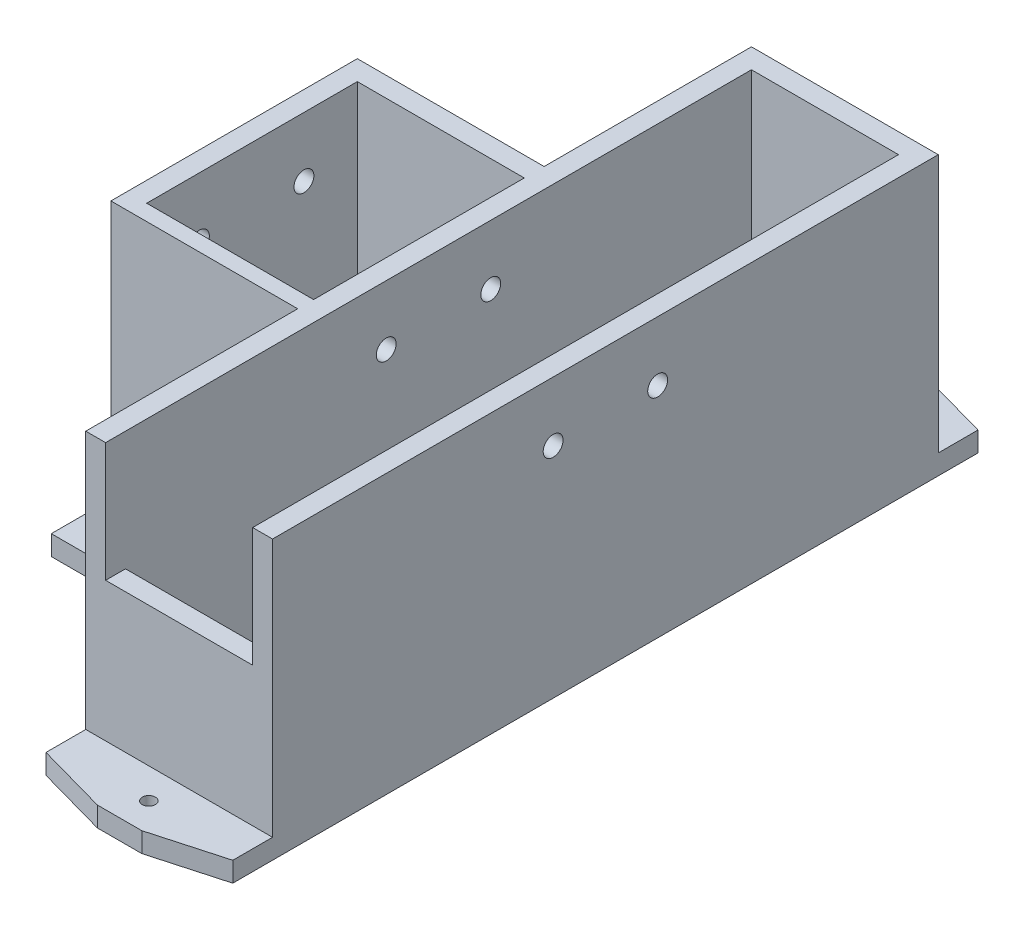
SolidWorks part; units mm, degrees
ref_plane "Plano frontal" through (0, 0, 0) normal (0, 0, 1) x (1, 0, 0)
ref_plane "Plano superior" through (0, 0, 0) normal (0, 1, 0) x (1, 0, 0)
ref_plane "Plano direito" through (0, 0, 0) normal (1, 0, 0) x (0, 0, -1)
sketch "Esboço1" plane through (0, 0, 0) normal (0, 1, 0) x (1, 0, 0)
  line L0 (9.0777, 0.5851) -> (55.4959, 0.5851) construction
  line L1 (0, 0) -> (0, -30.0205) construction
  line L3 (-23.5, 83.75) -> (23.5, 83.75)
  line L4 (-23.5, 83.75) -> (-23.5, -83.75)
  line L5 (-23.5, -83.75) -> (23.5, -83.75)
  line L6 (23.5, 83.75) -> (23.5, -83.75)
  line L7 (-23.5, 83.75) -> (23.5, -83.75) construction
  line L8 (-23.5, -83.75) -> (23.5, 83.75) construction
  line L9 (-70.5, 31.5851) -> (-23.5, 31.5851)
  line L10 (-70.5, 31.5851) -> (-70.5, -30.4149)
  line L11 (-70.5, -30.4149) -> (-23.5, -30.4149)
  line L12 (-23.5, 31.5851) -> (-23.5, -30.4149)
  line L13 (-70.5, 31.5851) -> (-23.5, -30.4149) construction
  line L14 (-70.5, -30.4149) -> (-23.5, 31.5851) construction
  point P1 (0, 0)
  point P11 (-47, 0.5851)
  dimension "D1" = 47
  dimension "D2" = 167.5
  dimension "D3" = 47
  dimension "D4" = 62
extrude "Ressalto-extrusão1" add sketch "Esboço1" along normal blind 70 contours L10 L11 L4 L9 | L6 L3 L4 L5
sketch "Esboço3" plane through (0, 70, 0) normal (0, 1, 0) x (1, 0, 0)
  line L0 (-23.5, 83.75) -> (23.5, 83.75) construction
  line L1 (18.5, -78.75) -> (-18.5, -78.75)
  line L2 (18.5, -78.75) -> (18.5, 78.75)
  line L3 (18.5, 78.75) -> (-18.5, 78.75)
  line L4 (-18.5, -78.75) -> (-18.5, 78.75)
  line L5 (18.5, -78.75) -> (-18.5, 78.75) construction
  line L6 (18.5, 78.75) -> (-18.5, -78.75) construction
  line L7 (-23.5, 83.75) -> (-23.5, 31.5851) construction
  point P0 (0, 0)
  dimension "D1" = 157.5
  dimension "D2" = 5
  dimension "D3" = 37
  dimension "D4" = 5
extrude "Corte-extrusão2" cut sketch "Esboço3" against normal blind 65
sketch "Esboço5" plane through (0, 70, 0) normal (0, 1, 0) x (1, 0, 0)
  line L0 (-18.5, -78.75) -> (18.5, -78.75) construction
  line L1 (-18.5, -62.7828) -> (18.5, -62.7828)
  line L2 (-18.5, -62.7828) -> (-18.5, -94.7172)
  line L3 (-18.5, -94.7172) -> (18.5, -94.7172)
  line L4 (18.5, -62.7828) -> (18.5, -94.7172)
  line L5 (-18.5, -62.7828) -> (18.5, -94.7172) construction
  line L6 (-18.5, -94.7172) -> (18.5, -62.7828) construction
  point P0 (0, -78.75)
  dimension "D1" = 37
extrude "Corte-extrusão3" cut sketch "Esboço5" against normal blind 30
sketch "Esboço11" plane through (0, 0, 0) normal (0, -1, 0) x (1, 0, 0)
  line L0 (-23.5, -83.75) -> (-23.5, -31.5851) construction
  line L1 (-23.5, -83.75) -> (23.5, -83.75)
  line L2 (-23.5, -83.75) -> (-23.5, -98.75)
  line L3 (-23.5, -98.75) -> (23.5, -98.75)
  line L4 (23.5, -83.75) -> (23.5, -98.75)
  line L5 (-23.5, 83.75) -> (23.5, 83.75)
  line L6 (-23.5, 83.75) -> (-23.5, 98.75)
  line L7 (-23.5, 98.75) -> (23.5, 98.75)
  line L8 (23.5, 83.75) -> (23.5, 98.75)
  line L9 (-70.5, -31.5851) -> (-23.5, -31.5851)
  line L10 (-70.5, -31.5851) -> (-70.5, -46.5851)
  line L11 (-70.5, -46.5851) -> (-23.5, -46.5851)
  line L12 (-23.5, -31.5851) -> (-23.5, -46.5851)
  line L13 (-23.5, 30.4149) -> (-23.5, 83.75) construction
  line L14 (-70.5, 30.4149) -> (-23.5, 30.4149)
  line L15 (-70.5, 30.4149) -> (-70.5, 45.4149)
  line L16 (-70.5, 45.4149) -> (-23.5, 45.4149)
  line L17 (-23.5, 30.4149) -> (-23.5, 45.4149)
  dimension "D1" = 15
  dimension "D2" = 15
  dimension "D3" = 15
  dimension "D4" = 15
extrude "Ressalto-extrusão2" add sketch "Esboço11" against normal blind 5
sketch "Esboço12" plane through (0, 5, 0) normal (0, 1, 0) x (1, 0, 0)
  line L0 (-70.5, 46.5851) -> (-23.5, 46.5851) construction
  line L1 (-23.5, -45.4149) -> (-70.5, -45.4149) construction
  line L2 (-70.5, 31.5851) -> (-70.5, 46.5851) construction
  line L4 (-70.5, -45.4149) -> (-70.5, -30.4149) construction
  line L5 (23.5, -98.75) -> (-23.5, -98.75) construction
  line L6 (-23.5, 98.75) -> (23.5, 98.75) construction
  circle A0 centre (-47, -38.0499) radius 1.65
  circle A2 centre (-47, 39.2151) radius 1.65
  circle A4 centre (0, -91.38) radius 1.65
  circle A5 centre (0, 91.38) radius 1.65
  point P20 (0, -98.75)
  dimension "D1" = 3.3
  dimension "D5" = 3.3
  dimension "D11" = 3.3
  dimension "D13" = 3.3
  dimension "D4" = 7.37
  dimension "D8" = 7.365
  dimension "D9" = 23.5
  dimension "D10" = 23.5
  dimension "D12" = 7.37
  dimension "D14" = 7.37
extrude "Corte-extrusão6" cut sketch "Esboço12" against normal through all
sketch "Esboço14" plane through (23.5, 0, 0) normal (1, 0, 0) x (0, 0, -1)
  line L0 (0, 0) -> (0, 98.479) construction
  line L1 (83.75, 70) -> (-83.75, 70) construction
  circle A0 centre (-13.15, 55) radius 2.5
  circle A1 centre (13.15, 55) radius 2.5
  dimension "D1" = 26.3
  dimension "D2" = 5
  dimension "D3" = 5
  dimension "D4" = 13.15
  dimension "D5" = 15
  dimension "D6" = 15
extrude "Corte-extrusão8" cut sketch "Esboço14" against normal through all
sketch "Esboço15" plane through (0, 70, 0) normal (0, 1, 0) x (1, 0, 0)
  line L1 (-65.5, 26.5851) -> (-23.5, 26.5851)
  line L2 (-65.5, 26.5851) -> (-65.5, -26.4149)
  line L3 (-65.5, -26.4149) -> (-23.5, -26.4149)
  line L4 (-23.5, 26.5851) -> (-23.5, -26.4149)
  line L5 (-65.5, 26.5851) -> (-23.5, -26.4149) construction
  line L6 (-65.5, -26.4149) -> (-23.5, 26.5851) construction
  line L7 (-70.5, 31.5851) -> (-23.5, 31.5851) construction
  line L8 (-18.5, 78.75) -> (-18.5, -83.75) construction
  point P0 (-44.5, 0.0851)
  dimension "D1" = 42
  dimension "D2" = 5
  dimension "D3" = 53
  dimension "D4" = 5
extrude "Corte-extrusão10" cut sketch "Esboço15" against normal blind 65
chamfer "Chanfro9" distance 5 angle 74.4 4 edges at (23.5, 2.5, 98.75) (-23.5, 2.5, 98.75) (-23.5, 2.5, -98.75) (23.5, 2.5, -98.75)
